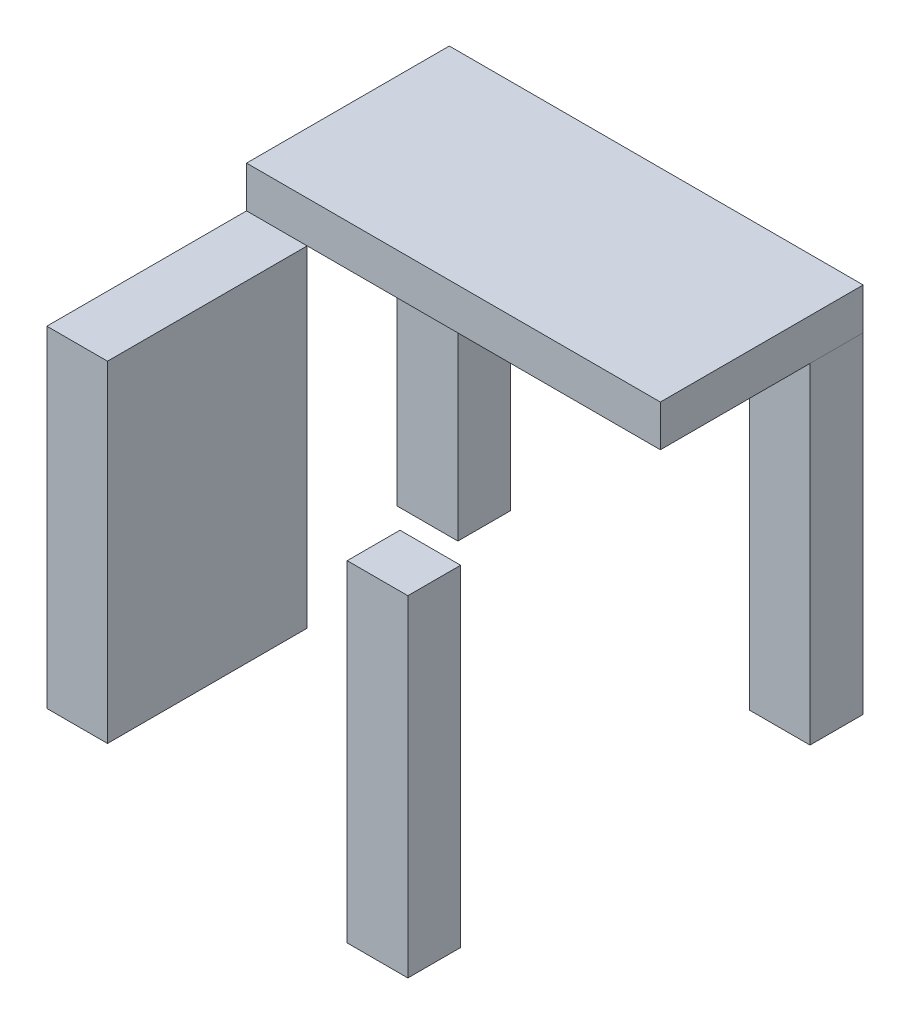
SolidWorks part; units mm, degrees
ref_plane "Front Plane" through (0, 0, 0) normal (0, 0, 1) x (1, 0, 0)
ref_plane "Top Plane" through (0, 0, 0) normal (0, 1, 0) x (1, 0, 0)
ref_plane "Right Plane" through (0, 0, 0) normal (1, 0, 0) x (0, 0, -1)
sketch "Sketch1" plane through (0, 0, 0) normal (0, 0, 1) x (1, 0, 0)
  line L1 (0, 0) -> (100, 0)
  line L2 (0, 0) -> (0, 10)
  line L3 (0, 10) -> (100, 10)
  line L4 (100, 0) -> (100, 10)
  dimension "D1" = 10
  dimension "D2" = 100
extrude "Boss-Extrude1" add sketch "Sketch1" along normal blind 49
sketch "Sketch2" plane through (0, 0, 0) normal (0, -1, 0) x (1, 0, 0)
  line L0 (85.3618, 110.0347) -> (100.0191, 110.0347)
  line L1 (0, 49) -> (14.6573, 49)
  line L2 (0, 49) -> (0, 97.2496)
  line L3 (0, 97.2496) -> (14.6573, 97.2496)
  line L4 (14.6573, 49) -> (14.6573, 97.2496)
  line L5 (85.3618, 110.0347) -> (85.3618, 97.2843)
  line L6 (85.3618, 97.2843) -> (100.0191, 97.2843)
  line L7 (100.0191, 110.0347) -> (100.0191, 97.2843)
  line L8 (-0.0191, 12.5688) -> (14.6382, 12.5688)
  line L9 (-0.0191, 12.5688) -> (-0.0191, -0.1816)
  line L10 (-0.0191, -0.1816) -> (14.6382, -0.1816)
  line L11 (14.6382, 12.5688) -> (14.6382, -0.1816)
  line L12 (85.2149, 12.7157) -> (99.8722, 12.7157)
  line L13 (85.2149, 12.7157) -> (85.2149, -0.0347)
  line L14 (85.2149, -0.0347) -> (99.8722, -0.0347)
  line L15 (99.8722, 12.7157) -> (99.8722, -0.0347)
extrude "Boss-Extrude2" add sketch "Sketch2" along normal blind 80
equation "\"LTest\" = 49mm"
equation "\"D1@Boss-Extrude1\"=\"LTest\""
